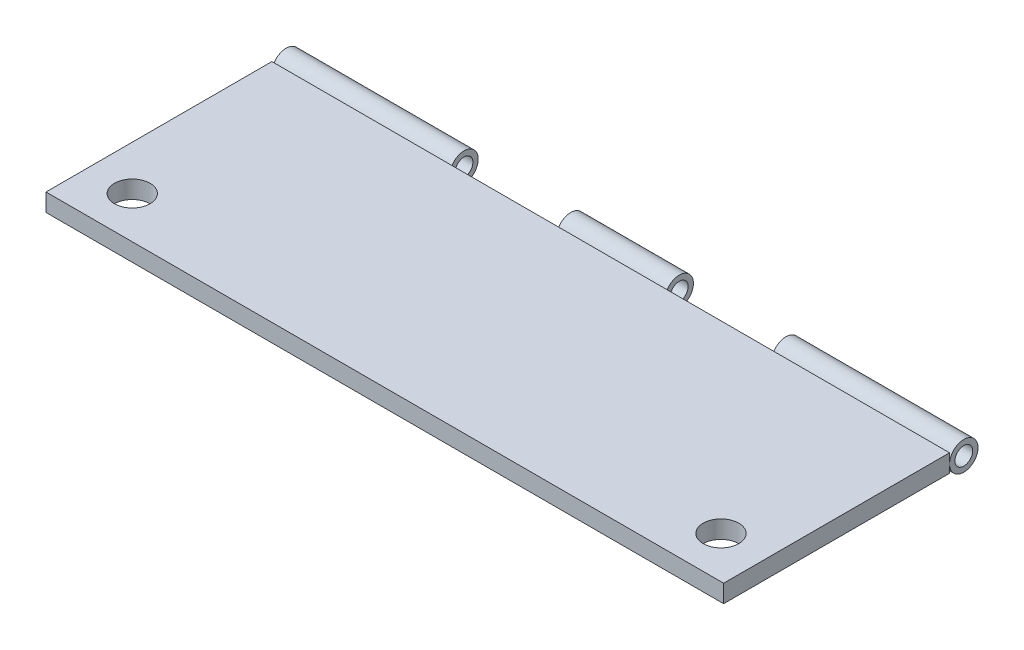
SolidWorks part; units mm, degrees
ref_plane "Alzado" through (0, 0, 0) normal (0, 0, 1) x (1, 0, 0)
ref_plane "Planta" through (0, 0, 0) normal (0, 1, 0) x (1, 0, 0)
ref_plane "Vista lateral" through (0, 0, 0) normal (1, 0, 0) x (0, 0, -1)
sketch "Croquis1" plane through (0, 0, 0) normal (0, 1, 0) x (1, 0, 0)
  line L1 (-38.1, -12.7) -> (38.1, -12.7)
  line L2 (-38.1, -12.7) -> (-38.1, 12.7)
  line L3 (-38.1, 12.7) -> (38.1, 12.7)
  line L4 (38.1, -12.7) -> (38.1, 12.7)
  line L5 (-38.1, -12.7) -> (38.1, 12.7) construction
  line L6 (-38.1, 12.7) -> (38.1, -12.7) construction
  point P0 (0, 0)
  dimension "D1" = 76.2
  dimension "D2" = 25.4
extrude "Saliente-Extruir1" add sketch "Croquis1" along normal blind 2
sketch "Croquis2" plane through (-38.1, 0, 0) normal (-1, 0, 0) x (0, 0, 1)
  circle A0 centre (-14.3062, 0.901) radius 1.6
extrude "Saliente-Extruir2" add sketch "Croquis2" against normal up to surface (76.2 mm away) separate body up to face at (38.1, 1, 0)
sketch "Croquis3" plane through (0, 2, 0) normal (0, 1, 0) x (1, 0, 0)
  line L0 (-38.1, 0) -> (-33.1, 0)
  line L1 (-38.1, 12.7) -> (-38.1, -12.7) construction
  line L2 (-33.1, 0) -> (-33.1, -8)
  line L3 (38.1, 0) -> (33.1, 0)
  line L4 (38.1, -12.7) -> (38.1, 12.7) construction
  line L5 (33.1, 0) -> (33.1, -8)
  circle A0 centre (-33.1, -8) radius 2
  circle A1 centre (33.1, -8) radius 2
extrude "Cortar-Extruir1" cut sketch "Croquis3" against normal blind 2
sketch "Croquis4" plane through (-38.1, 0, 0) normal (-1, 0, 0) x (0, 0, 1)
  circle A0 centre (-14.3062, 0.901) radius 1
extrude "Cortar-Extruir2" cut sketch "Croquis4" against normal up to surface (76.2 mm away) up to face at (38.1, 0.901, -12.7062)
sketch "Croquis5" plane through (0, 2, 0) normal (0, 1, 0) x (1, 0, 0)
  line L0 (-38.1, 14.3062) -> (-18.1, 14.3062)
  line L1 (-38.1, 15.9062) -> (-38.1, 12.7062) construction
  line L2 (38.1, 14.3062) -> (18.1, 14.3062)
  line L3 (38.1, 12.7062) -> (38.1, 15.9062) construction
  line L4 (-18.1, 14.3062) -> (-6.1, 14.3062)
  line L5 (18.1, 14.3062) -> (6.1, 14.3062)
  line L6 (38.1, 15.9062) -> (-38.1, 15.9062) construction
  line L7 (-18.1, 12.7062) -> (-6.1, 12.7062)
  line L8 (-18.1, 12.7062) -> (-18.1, 15.9062)
  line L9 (-18.1, 15.9062) -> (-6.1, 15.9062)
  line L10 (-6.1, 12.7062) -> (-6.1, 15.9062)
  line L11 (-18.1, 12.7062) -> (-6.1, 15.9062) construction
  line L12 (-18.1, 15.9062) -> (-6.1, 12.7062) construction
  line L13 (38.1, 15.9062) -> (-38.1, 15.9062) construction
  line L14 (6.1, 12.7062) -> (18.1, 12.7062)
  line L15 (6.1, 12.7062) -> (6.1, 15.9062)
  line L16 (6.1, 15.9062) -> (18.1, 15.9062)
  line L17 (18.1, 12.7062) -> (18.1, 15.9062)
  line L18 (6.1, 12.7062) -> (18.1, 15.9062) construction
  line L19 (6.1, 15.9062) -> (18.1, 12.7062) construction
  point P8 (-12.1, 14.3062)
  point P17 (12.1, 14.3062)
  dimension "D1" = 20
  dimension "D2" = 12
  dimension "D3" = 12
  dimension "D4" = 20
extrude "Cortar-Extruir4" cut sketch "Croquis5" against normal up to surface (2 mm away) and the other way up to surface contours L5 L17 L16 L15 | L14 L17 L5 L15 | L9 L10 L7 L8 other way up to face at (38.1, 0.901, -12.7062)
